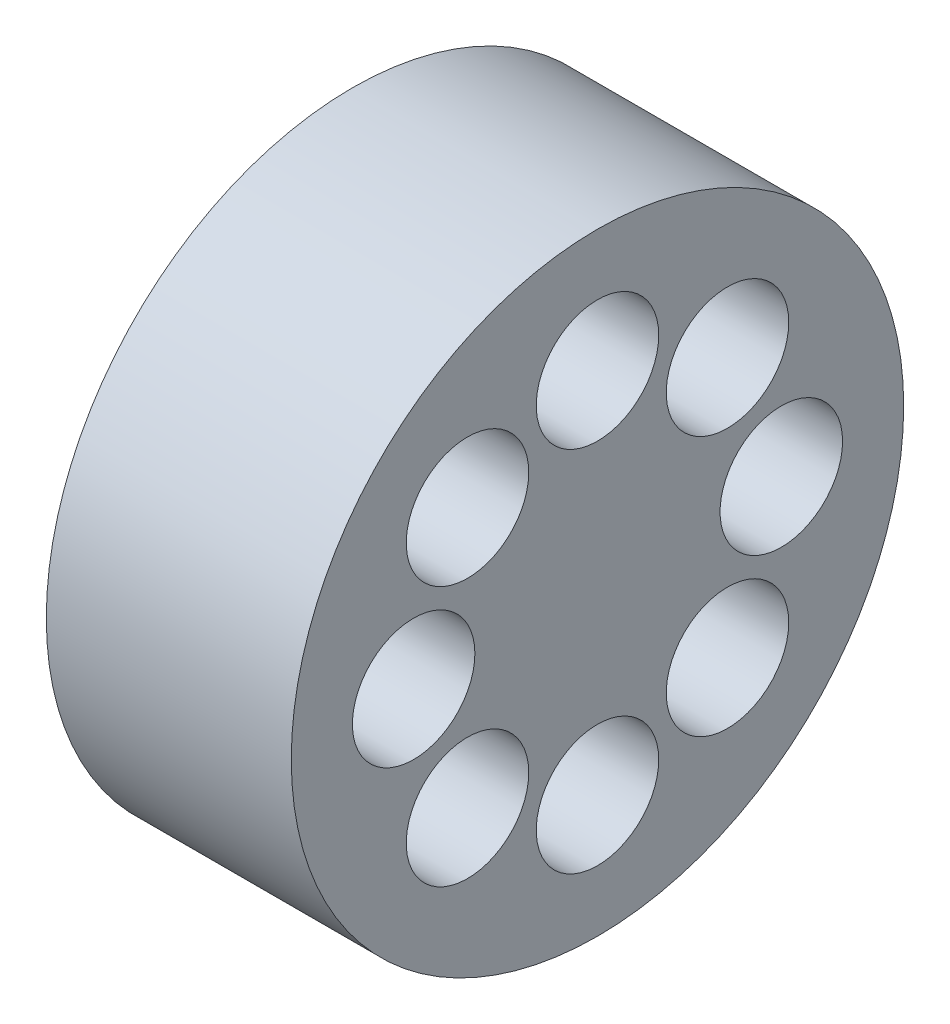
SolidWorks part; units mm, degrees
ref_plane "Front Plane" through (0, 0, 0) normal (0, 0, 1) x (1, 0, 0)
ref_plane "Top Plane" through (0, 0, 0) normal (0, 1, 0) x (1, 0, 0)
ref_plane "Right Plane" through (0, 0, 0) normal (1, 0, 0) x (0, 0, -1)
sketch "Sketch1" plane through (0, 0, 0) normal (1, 0, 0) x (0, 0, -1)
  circle A0 centre (0, 0) radius 50
  circle A1 centre (30.019, 0) radius 10
  circle A2 centre (21.2267, -21.2267) radius 10
  circle A3 centre (0, -30.019) radius 10
  circle A4 centre (-21.2267, -21.2267) radius 10
  circle A5 centre (-30.019, 0) radius 10
  circle A6 centre (-21.2267, 21.2267) radius 10
  circle A7 centre (0, 30.019) radius 10
  circle A8 centre (21.2267, 21.2267) radius 10
  point P21 (0, 0)
  dimension "D1" = 8
extrude "Boss-Extrude1" add sketch "Sketch1" along normal blind 40
